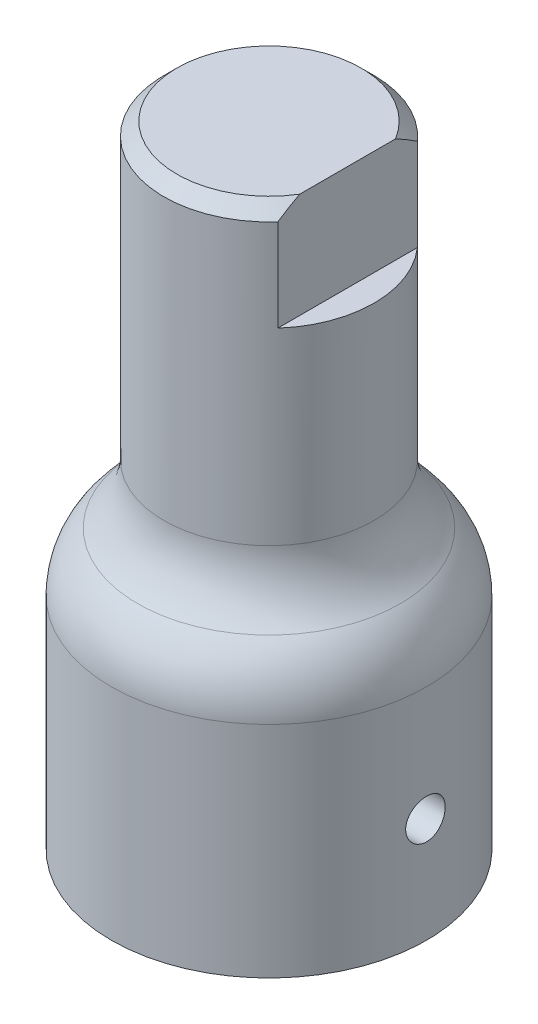
SolidWorks part; units mm, degrees
ref_plane "정면" through (0, 0, 0) normal (0, 0, 1) x (1, 0, 0)
ref_plane "윗면" through (0, 0, 0) normal (0, 1, 0) x (1, 0, 0)
ref_plane "우측면" through (0, 0, 0) normal (1, 0, 0) x (0, 0, -1)
sketch "스케치1" plane through (0, 0, 0) normal (0, 0, 1) x (1, 0, 0)
  line L0 (6.35, 38.1) -> (0, 38.1)
  line L1 (0, 38.1) -> (0, 0)
  line L2 (0, 0) -> (9.525, 0)
  line L3 (9.525, 0) -> (9.525, 13.2632)
  line L4 (6.35, 20.3741) -> (6.35, 38.1)
  line L5 (0, 38.1) -> (0, 0) construction
  arc A0 (9.525, 13.2632) -> (7.9375, 16.8187) centre (4.7498, 13.2632) ccw
  arc A1 (7.9375, 16.8187) -> (6.35, 20.3741) centre (11.1252, 20.3741) cw
revolve "회전1" add sketch "스케치1" angle 360 about L5
sketch "스케치2" plane through (0, 38.1, 0) normal (0, 1, 0) x (-1, 0, 0)
  line L0 (-4.7498, -4.2145) -> (-4.7498, 4.2145)
  arc A0 (-4.7498, 4.2145) -> (-4.7498, -4.2145) centre (0, 0) ccw
extrude "컷-돌출1" cut sketch "스케치2" against normal blind 6.35
sketch "스케치3" plane through (0, 0, 0) normal (0, -1, 0) x (1, 0, 0)
  line L0 (4.7498, -4.2145) -> (4.7498, 4.2145)
  arc A0 (4.7498, 4.2145) -> (4.7498, -4.2145) centre (0, 0) ccw
extrude "컷-돌출2" cut sketch "스케치3" against normal blind 12.7
hole_wizard "M2 여유 구멍1" positions "스케치5" profile "스케치4" hole size "M2" standard "Ansi Metric"
sketch "스케치5" plane through (4.7498, 0, 0) normal (-1, 0, 0) x (0, 0, 1)
  point P0 (0, 6.35)
sketch "스케치4" plane through (4.7498, 6.35, 0) normal (0, 1, 0) x (0, 0, 1)
  line L0 (0, 0) -> (0, 4.7752)
  line L1 (0, 4.7752) -> (1.1938, 4.7752)
  line L2 (1.1938, 4.7752) -> (1.1938, 0)
  line L5 (1.1938, 0) -> (0, 0)
  line L11 (0, -6.35) -> (0, 107.95) construction
  dimension "관통 구멍 지름" = 2.3876
  dimension "관통 구멍 깊이" = 4.7752
chamfer "모따기1" distance 0.7874 angle 45 1 edges at (-6.35, 38.1, 0)
